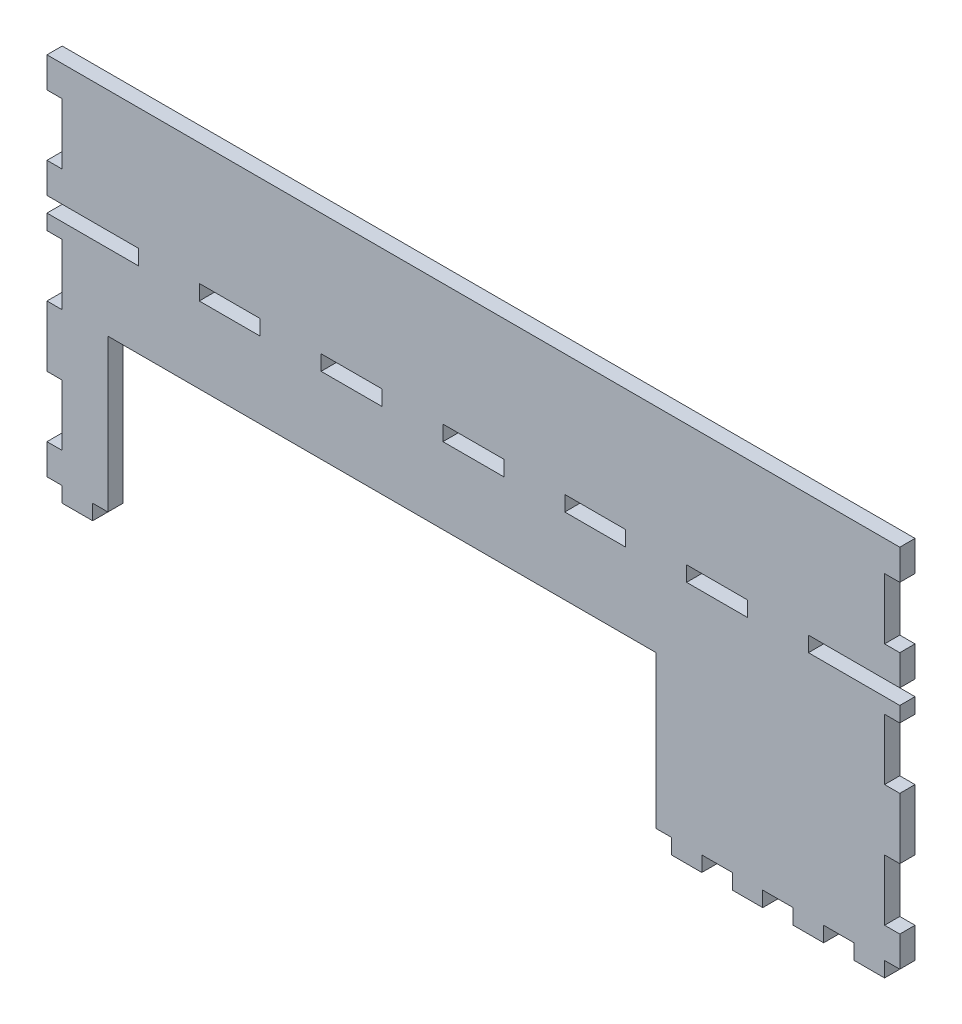
SolidWorks part; units mm, degrees
material "Pin"
ref_plane "Front" through (0, 0, 0) normal (0, 0, 1) x (1, 0, 0)
ref_plane "Top" through (0, 0, 0) normal (0, 1, 0) x (1, 0, 0)
ref_plane "Right" through (0, 0, 0) normal (1, 0, 0) x (0, 0, -1)
sketch "Esquisse1" plane through (0, 0, 0) normal (0, 0, 1) x (1, 0, 0)
  line L1 (-177.8, 76.2) -> (177.8, 76.2)
  line L2 (-177.8, 76.2) -> (-177.8, -76.2)
  line L3 (-177.8, -76.2) -> (177.8, -76.2)
  line L4 (177.8, 76.2) -> (177.8, -76.2)
  line L5 (-177.8, 76.2) -> (177.8, -76.2) construction
  line L6 (-177.8, -76.2) -> (177.8, 76.2) construction
  point P0 (0, 0)
  dimension "D1" = 355.6
  dimension "D2" = 152.4
extrude "Boss.-Extru.1" add sketch "Esquisse1" along normal blind 6.35
sketch "Esquisse3" plane through (0, 0, 6.35) normal (0, 0, 1) x (1, 0, 0)
  line L0 (-177.8, 76.2) -> (-177.8, -76.2) construction
  line L1 (177.8, 76.2) -> (-177.8, 76.2) construction
  line L2 (-177.8, 63.5) -> (-171.45, 63.5)
  line L3 (-177.8, 63.5) -> (-177.8, 38.1)
  line L4 (-177.8, 38.1) -> (-171.45, 38.1)
  line L5 (-171.45, 63.5) -> (-171.45, 38.1)
  dimension "D1" = 6.35
  dimension "D2" = 25.4
  dimension "D3" = 12.7
extrude "Enlèv. mat.-Extru.2" cut sketch "Esquisse3" against normal blind 6.35
pattern_linear "Répétition linéaire2" count 3 spacing 50.8 along (0, -1, 0) of "Enlèv. mat.-Extru.2"
mirror "Symétrie1" about plane through (0, 0, 0) normal (1, 0, 0) of "Répétition linéaire2", "Enlèv. mat.-Extru.2"
sketch "Sketch1" plane through (0, 0, 6.35) normal (0, 0, 1) x (1, 0, 0)
  line L0 (-177.8, -76.2) -> (177.8, -76.2) construction
  line L1 (-152.4, -76.2) -> (76.2, -76.2)
  line L2 (-152.4, -76.2) -> (-152.4, -12.7)
  line L3 (-152.4, -12.7) -> (76.2, -12.7)
  line L4 (76.2, -76.2) -> (76.2, -12.7)
  line L5 (-171.45, -63.5) -> (-171.45, -38.1) construction
  dimension "D1" = 63.5
  dimension "D2" = 228.6
  dimension "D3" = 19.05
extrude "Cut-Extrude1" cut sketch "Sketch1" against normal up to next
sketch "Esquisse5" plane through (0, 0, 6.35) normal (0, 0, 1) x (1, 0, 0)
  line L0 (-177.8, 38.1) -> (-177.8, 12.7) construction
  line L1 (-177.8, 25.4) -> (-139.7, 25.4)
  line L2 (-177.8, 25.4) -> (-177.8, 19.05)
  line L3 (-177.8, 19.05) -> (-139.7, 19.05)
  line L4 (-139.7, 25.4) -> (-139.7, 19.05)
  line L5 (-177.8, -76.2) -> (-152.4, -76.2) construction
  dimension "D1" = 6.35
  dimension "D2" = 38.1
  dimension "D3" = 95.25
extrude "Enlèv. mat.-Extru.4" cut sketch "Esquisse5" against normal blind 6.35
mirror "Symétrie2" about plane through (0, 0, 0) normal (1, 0, 0) of "Enlèv. mat.-Extru.4"
sketch "Esquisse6" plane through (0, 0, 6.35) normal (0, 0, 1) x (1, 0, 0)
  line L0 (-139.7, 19.05) -> (-139.7, 25.4) construction
  line L1 (-114.3, 19.05) -> (-88.9, 19.05)
  line L2 (-114.3, 19.05) -> (-114.3, 25.4)
  line L3 (-114.3, 25.4) -> (-88.9, 25.4)
  line L4 (-88.9, 19.05) -> (-88.9, 25.4)
  line L5 (-177.8, 19.05) -> (-139.7, 19.05) construction
  dimension "D1" = 6.35
  dimension "D2" = 25.4
  dimension "D3" = 25.4
extrude "Enlèv. mat.-Extru.5" cut sketch "Esquisse6" against normal blind 6.35
pattern_linear "Répétition linéaire3" count 5 spacing 50.8 along (1, 0, 0) of "Enlèv. mat.-Extru.5"
sketch "Esquisse8" plane through (0, 0, 6.35) normal (0, 0, 1) x (1, 0, 0)
  line L0 (-177.8, -76.2) -> (-152.4, -76.2) construction
  line L1 (-177.8, -63.5) -> (-177.8, -76.2) construction
  line L2 (-171.45, -76.2) -> (-158.75, -76.2)
  line L3 (-171.45, -76.2) -> (-171.45, -82.55)
  line L4 (-171.45, -82.55) -> (-158.75, -82.55)
  line L5 (-158.75, -76.2) -> (-158.75, -82.55)
  line L6 (76.2, -76.2) -> (177.8, -76.2) construction
  line L7 (82.55, -76.2) -> (95.25, -76.2)
  line L8 (82.55, -76.2) -> (82.55, -82.55)
  line L9 (82.55, -82.55) -> (95.25, -82.55)
  line L10 (95.25, -76.2) -> (95.25, -82.55)
  line L11 (76.2, -76.2) -> (76.2, -12.7) construction
  line L12 (107.95, -76.2) -> (120.65, -76.2)
  line L13 (107.95, -76.2) -> (107.95, -82.55)
  line L14 (107.95, -82.55) -> (120.65, -82.55)
  line L15 (120.65, -76.2) -> (120.65, -82.55)
  line L16 (133.35, -76.2) -> (146.05, -76.2)
  line L17 (133.35, -76.2) -> (133.35, -82.55)
  line L18 (133.35, -82.55) -> (146.05, -82.55)
  line L19 (146.05, -76.2) -> (146.05, -82.55)
  line L20 (158.75, -76.2) -> (171.45, -76.2)
  line L21 (158.75, -76.2) -> (158.75, -82.55)
  line L22 (158.75, -82.55) -> (171.45, -82.55)
  line L23 (171.45, -76.2) -> (171.45, -82.55)
  dimension "D1" = 6.35
  dimension "D2" = 12.7
  dimension "D3" = 6.35
  dimension "D4" = 6.35
  dimension "D5" = 12.7
  dimension "D6" = 6.35
  dimension "D7" = 4
extrude "Boss.-Extru.2" add sketch "Esquisse8" against normal blind 6.35
